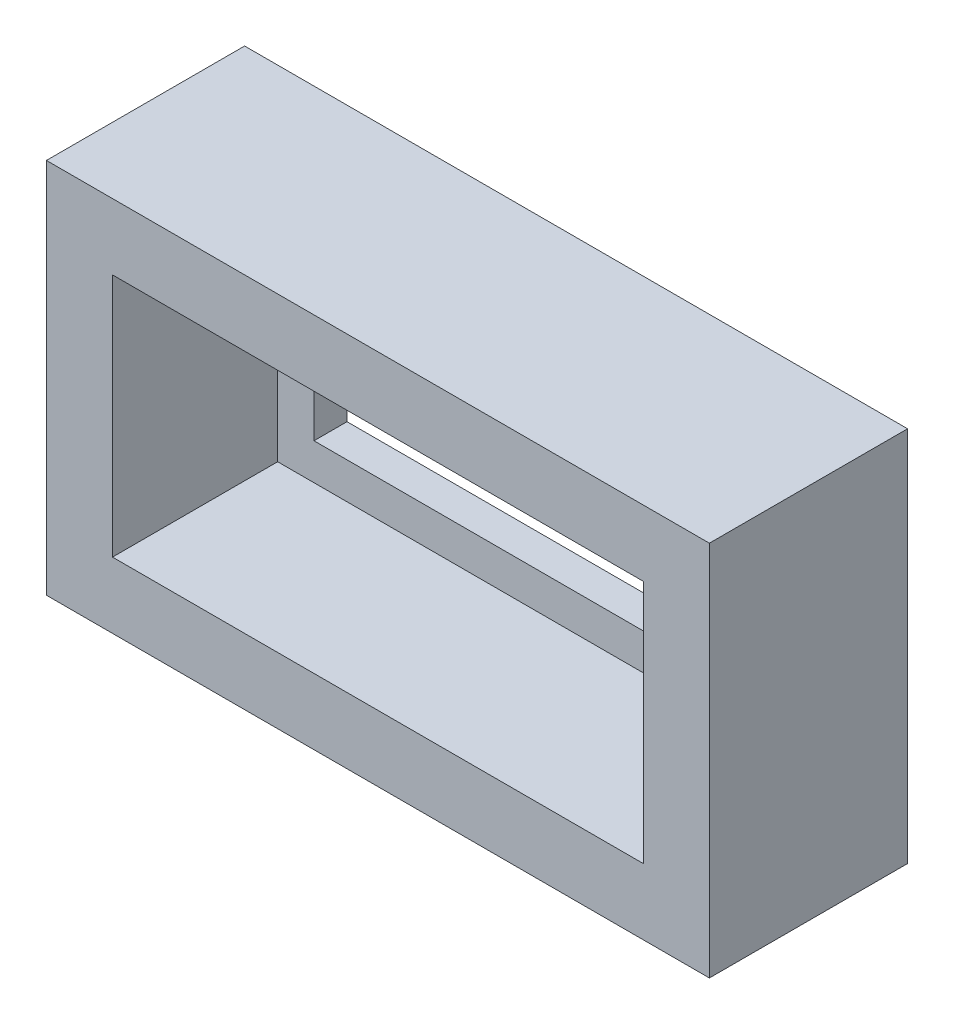
SolidWorks part; units mm, degrees
ref_plane "Front Plane" through (0, 0, 0) normal (0, 0, 1) x (1, 0, 0)
ref_plane "Top Plane" through (0, 0, 0) normal (0, 1, 0) x (1, 0, 0)
ref_plane "Right Plane" through (0, 0, 0) normal (1, 0, 0) x (0, 0, -1)
sketch "Sketch1" plane through (0, 0, 0) normal (0, 0, 1) x (1, 0, 0)
  line L1 (-8.035, -3.7) -> (8.035, -3.7)
  line L2 (-8.035, -3.7) -> (-8.035, 3.7)
  line L3 (-8.035, 3.7) -> (8.035, 3.7)
  line L4 (8.035, -3.7) -> (8.035, 3.7)
  line L5 (-8.035, -3.7) -> (8.035, 3.7) construction
  line L6 (-8.035, 3.7) -> (8.035, -3.7) construction
  line L7 (-10.035, -5.7) -> (10.035, -5.7)
  line L8 (-10.035, -5.7) -> (-10.035, 5.7)
  line L9 (-10.035, 5.7) -> (10.035, 5.7)
  line L10 (10.035, -5.7) -> (10.035, 5.7)
  line L11 (-10.035, -5.7) -> (10.035, 5.7) construction
  line L12 (-10.035, 5.7) -> (10.035, -5.7) construction
  point P0 (0, 0)
  point P6 (0, 0)
  dimension "D1" = 16.07
  dimension "D2" = 7.4
  dimension "D3" = 2
  dimension "D4" = 2
extrude "Boss-Extrude1" add sketch "Sketch1" along normal blind 6
sketch "Sketch2" plane through (0, 0, 0) normal (0, 0, -1) x (-1, 0, 0)
  line L1 (-8.035, -3.7) -> (8.035, -3.7)
  line L2 (-8.035, -3.7) -> (-8.035, 3.7)
  line L3 (-8.035, 3.7) -> (8.035, 3.7)
  line L4 (8.035, -3.7) -> (8.035, 3.7)
  line L5 (-8.035, -3.7) -> (8.035, 3.7) construction
  line L6 (-8.035, 3.7) -> (8.035, -3.7) construction
  line L7 (-6.935, -2.6) -> (6.935, -2.6)
  line L8 (-6.935, -2.6) -> (-6.935, 2.6)
  line L9 (-6.935, 2.6) -> (6.935, 2.6)
  line L10 (6.935, -2.6) -> (6.935, 2.6)
  line L11 (-6.935, -2.6) -> (6.935, 2.6) construction
  line L12 (-6.935, 2.6) -> (6.935, -2.6) construction
  point P0 (0, 0)
  point P7 (0, 0)
  dimension "D1" = 1.1
  dimension "D2" = 1.1
extrude "Boss-Extrude2" add sketch "Sketch2" against normal blind 1
sketch "Sketch3" plane through (0, 0, 1) normal (0, 0, 1) x (1, 0, 0)
  line L0 (-8.035, 3.7) -> (-8.035, -3.7) construction
  line L1 (-8.035, 3.11) -> (-6.915, 3.11)
  line L2 (-8.035, 3.11) -> (-8.035, 3.7)
  line L3 (-8.035, 3.7) -> (-6.915, 3.7)
  line L4 (-6.915, 3.11) -> (-6.915, 3.7)
  line L5 (8.035, 3.7) -> (-8.035, 3.7) construction
  line L6 (-8.035, -3.7) -> (8.035, -3.7) construction
  line L7 (6.915, -3.7) -> (8.035, -3.7)
  line L8 (6.915, -3.7) -> (6.915, -3.11)
  line L9 (6.915, -3.11) -> (8.035, -3.11)
  line L10 (8.035, -3.7) -> (8.035, -3.11)
  line L11 (8.035, -3.7) -> (8.035, 3.7) construction
  dimension "D1" = 1.12
  dimension "D2" = 0.59
  dimension "D3" = 1.12
  dimension "D4" = 0.59
extrude "Cut-Extrude1" cut sketch "Sketch3" against normal blind 1
